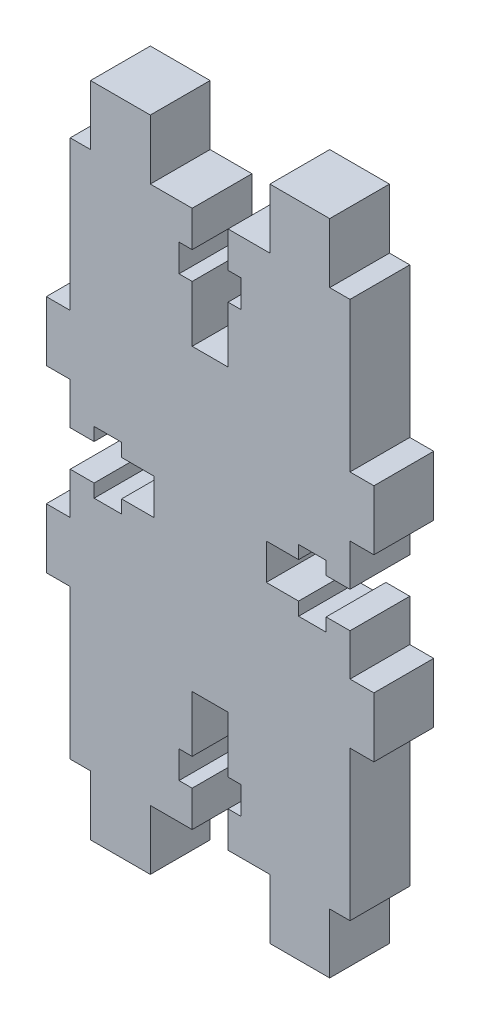
SolidWorks part; units mm, degrees
ref_plane "Plan de face" through (0, 0, 0) normal (0, 0, 1) x (1, 0, 0)
ref_plane "Plan de dessus" through (0, 0, 0) normal (0, 1, 0) x (1, 0, 0)
ref_plane "Plan de droite" through (0, 0, 0) normal (1, 0, 0) x (0, 0, -1)
sketch "Esquisse1" plane through (0, 0, 0) normal (0, 0, 1) x (1, 0, 0)
  line L0 (0, 0) -> (0, 45) construction
  line L1 (0, 45) -> (23.4, 45) construction
  line L2 (23.4, 45) -> (23.4, 0) construction
  line L3 (23.4, 0) -> (0, 0) construction
  line L4 (0, 22.5) -> (23.4, 22.5) construction
  line L5 (1.7, 45) -> (0, 45)
  line L6 (0, 45) -> (0, 32.5)
  line L7 (21.7, 45) -> (23.4, 45)
  line L8 (23.4, 45) -> (23.4, 32.5)
  line L9 (23.4, 12.5) -> (23.4, 0)
  line L10 (0, 0) -> (1.7, 0)
  line L11 (21.7, 0) -> (23.4, 0)
  line L12 (0, 0) -> (0, 12.5)
  line B0 (9.1, 3) -> (9.1, 5.3)
  line B1 (13.2, 5.3) -> (13.2, 10)
  line B2 (10.2, 10) -> (10.2, 5.3)
  line B3 (9.1, 5.3) -> (10.2, 5.3)
  line B4 (11.7, 0) -> (11.7, 11.2208) construction
  line B5 (10.2, 0) -> (6.7, 0)
  line B6 (6.7, -5) -> (1.7, -5)
  line B7 (1.7, -5) -> (1.7, 0)
  line B8 (6.7, -5) -> (6.7, 0)
  line B9 (13.2, 0) -> (16.7, 0)
  line B10 (16.7, 0) -> (16.7, -5)
  line B11 (16.7, -5) -> (21.7, -5)
  line B12 (21.7, -5) -> (21.7, 0)
  line B13 (10.2, 0) -> (13.2, 0) construction
  line B14 (13.2, 0) -> (13.2, 3)
  line B15 (13.2, 5.3) -> (14.3, 5.3)
  line B16 (14.3, 3) -> (13.2, 3)
  line B17 (13.2, 10) -> (10.2, 10)
  line B18 (10.2, 3) -> (9.1, 3)
  line B19 (14.3, 5.3) -> (14.3, 3)
  line B20 (10.2, 3) -> (10.2, 0)
  line B21 (11.7, 10) -> (11.7, 0) construction
  line B22 (9.1, 42) -> (9.1, 39.7)
  line B23 (13.2, 39.7) -> (13.2, 35)
  line B24 (10.2, 35) -> (10.2, 39.7)
  line B25 (9.1, 39.7) -> (10.2, 39.7)
  line B26 (11.7, 45) -> (11.7, 33.7792) construction
  line B27 (10.2, 45) -> (6.7, 45)
  line B28 (6.7, 50) -> (1.7, 50)
  line B29 (1.7, 50) -> (1.7, 45)
  line B30 (6.7, 50) -> (6.7, 45)
  line B31 (13.2, 45) -> (16.7, 45)
  line B32 (16.7, 45) -> (16.7, 50)
  line B33 (16.7, 50) -> (21.7, 50)
  line B34 (21.7, 50) -> (21.7, 45)
  line B35 (10.2, 45) -> (13.2, 45) construction
  line B36 (13.2, 45) -> (13.2, 42)
  line B37 (13.2, 39.7) -> (14.3, 39.7)
  line B38 (14.3, 42) -> (13.2, 42)
  line B39 (13.2, 35) -> (10.2, 35)
  line B40 (10.2, 42) -> (9.1, 42)
  line B41 (14.3, 39.7) -> (14.3, 42)
  line B42 (10.2, 42) -> (10.2, 45)
  line B43 (11.7, 35) -> (11.7, 45) construction
  line B44 (23.3419, 22.5) -> (9.4468, 22.5) construction
  line B45 (23.4, 21) -> (23.4, 17.5)
  line B46 (25.4, 17.5) -> (25.4, 12.5)
  line B47 (25.4, 12.5) -> (23.4, 12.5)
  line B48 (25.4, 17.5) -> (23.4, 17.5)
  line B49 (23.4, 23.7928) -> (23.4, 27.5)
  line B50 (23.4, 27.5) -> (25.4, 27.5)
  line B51 (25.4, 27.5) -> (25.4, 32.5)
  line B52 (25.4, 32.5) -> (23.4, 32.5)
  line B53 (23.4, 21) -> (23.4, 24) construction
  line B54 (23.4, 24) -> (21.4, 24)
  line B55 (19.1, 24) -> (19.1, 25.1)
  line B56 (21.4, 19.9) -> (19.1, 19.9)
  line B57 (21.4, 25.1) -> (21.4, 24)
  line B58 (19.1, 24) -> (16.4, 24)
  line B59 (16.4, 24) -> (16.4, 21)
  line B60 (16.4, 21) -> (19.1, 21)
  line B61 (21.4, 21) -> (21.4, 19.9)
  line B62 (19.1, 25.1) -> (21.4, 25.1)
  line B63 (19.1, 19.9) -> (19.1, 21)
  line B64 (21.4, 21) -> (23.4, 21)
  line B65 (16.4, 22.5) -> (23.4, 22.5) construction
  line B66 (0.0581, 22.5) -> (13.9532, 22.5) construction
  line B67 (0, 21) -> (0, 17.5)
  line B68 (-2, 17.5) -> (-2, 12.5)
  line B69 (-2, 12.5) -> (0, 12.5)
  line B70 (-2, 17.5) -> (0, 17.5)
  line B71 (0, 23.7928) -> (0, 27.5)
  line B72 (0, 27.5) -> (-2, 27.5)
  line B73 (-2, 27.5) -> (-2, 32.5)
  line B74 (-2, 32.5) -> (0, 32.5)
  line B75 (0, 21) -> (0, 24) construction
  line B76 (0, 24) -> (2, 24)
  line B77 (4.3, 24) -> (4.3, 25.1)
  line B78 (2, 19.9) -> (4.3, 19.9)
  line B79 (2, 25.1) -> (2, 24)
  line B80 (4.3, 24) -> (7, 24)
  line B81 (7, 24) -> (7, 21)
  line B82 (7, 21) -> (4.3, 21)
  line B83 (2, 21) -> (2, 19.9)
  line B84 (4.3, 25.1) -> (2, 25.1)
  line B85 (4.3, 19.9) -> (4.3, 21)
  line B86 (2, 21) -> (0, 21)
  line B87 (7, 22.5) -> (0, 22.5) construction
  dimension "D1" = 23.4
  dimension "D3" = 45
sketch_block_instance "Insert M3 plots ep 5mm-1"
sketch_block "Insert M3 plots ep 5mm" parameters "D1"=10, "D2"=5, "D3"=5
sketch_block_instance "Decoupe Insert M3-4"
sketch_block "Decoupe Insert M3" parameters "D1"=5.2, "D2"=3, "D3"=2.3, "D4"=3, "D5"=10
sketch_block_instance "Insert M3 plots ep 5mm-13"
sketch_block_instance "Bloc1-1"
sketch_block "Bloc1" parameters "D1"=10, "D2"=5, "D3"=2
sketch_block_instance "Bloc3-3"
sketch_block "Bloc3" parameters "D1"=5.2, "D2"=3, "D3"=2.3, "D4"=2, "D5"=7
sketch_block_instance "Bloc1-3"
extrude "Boss.-Extru.1" add sketch "Esquisse1" along normal blind 5
